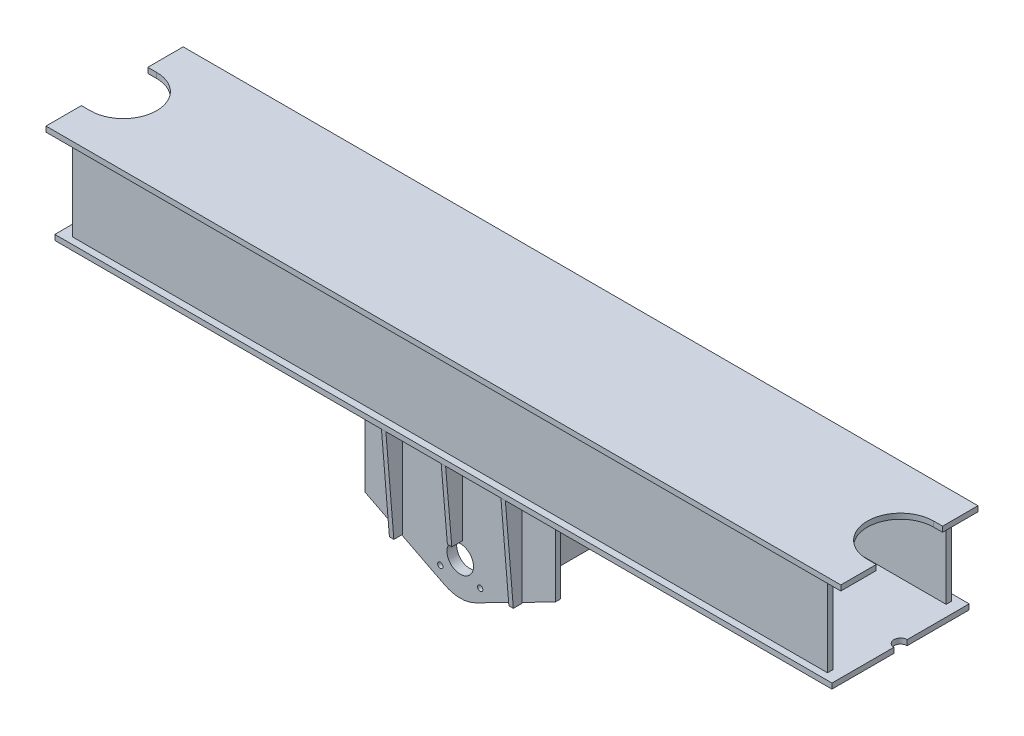
SolidWorks part; units mm, degrees
ref_plane "前视基准面" through (0, 0, 0) normal (0, 0, 1) x (1, 0, 0)
ref_plane "上视基准面" through (0, 0, 0) normal (0, 1, 0) x (1, 0, 0)
ref_plane "右视基准面" through (0, 0, 0) normal (1, 0, 0) x (0, 0, -1)
sketch "草图1" plane through (0, 0, 0) normal (0, 1, 0) x (1, 0, 0)
  line L0 (-1000, 0) -> (49000, 0) construction
  line L1 (0, -1000) -> (0, 49000) construction
  line L2 (-898, 155) -> (898, 155)
  line L3 (-898, -155) -> (898, -155)
  line L4 (898, 155) -> (898, 75)
  line L5 (898, 75) -> (878, 75)
  line L6 (898, -155) -> (898, -75)
  line L7 (878, -75) -> (898, -75)
  line L8 (-898, 155) -> (-898, 75)
  line L9 (-898, 75) -> (-878, 75)
  line L10 (-898, -155) -> (-898, -75)
  line L11 (-898, -75) -> (-878, -75)
  arc A0 (878, 75) -> (878, -75) centre (878, 0) ccw
  arc A1 (-878, 75) -> (-878, -75) centre (-878, 0) cw
  dimension "D3" = 75
  dimension "D5" = 75
  dimension "D1" = 1796
  dimension "D2" = 310
  dimension "D4" = 20
extrude "凸台-拉伸1" add sketch "草图1" along normal blind 12
sketch "草图2" plane through (0, 0, 0) normal (0, -1, 0) x (-1, 0, 0)
  line L0 (0, -1155) -> (0, 48845) construction
  line L1 (898, -155) -> (-898, -155) construction
  line L2 (-1000, 0) -> (49000, 0) construction
  line L3 (-853, 140) -> (853, 140)
  line L4 (853, -140) -> (-853, -140)
  line L5 (853, -140) -> (853, -128)
  line L6 (853, -128) -> (-853, -128)
  line L7 (-853, -140) -> (-853, -128)
  line L8 (-853, 140) -> (-853, 128)
  line L9 (-853, 128) -> (853, 128)
  line L10 (853, 140) -> (853, 128)
  point P5 (0, -155)
  dimension "D1" = 12
  dimension "D2" = 1706
  dimension "D3" = 256
extrude "凸台-拉伸2" add sketch "草图2" along normal blind 190
sketch "草图3" plane through (0, -190, 0) normal (0, -1, 0) x (1, 0, 0)
  line L0 (-898, 155) -> (898, 155) construction
  line L1 (-878, 155) -> (878, 155)
  line L2 (878, 155) -> (878, 15)
  line L3 (-878, -155) -> (878, -155)
  line L4 (878, -155) -> (878, -15)
  line L5 (898, -155) -> (-898, -155) construction
  line L6 (0, -1000) -> (0, 49000) construction
  line L7 (-1000, 0) -> (49000, 0) construction
  line L8 (-878, 155) -> (-878, 15)
  line L9 (-878, -15) -> (-878, -155)
  arc A0 (878, 15) -> (878, -15) centre (878, 0) ccw
  arc A1 (-878, 15) -> (-878, -15) centre (-878, 0) cw
  dimension "D3" = 15
  dimension "D4" = 15
  dimension "D1" = 1756
extrude "凸台-拉伸3" add sketch "草图3" along normal blind 12
sketch "草图4" plane through (0, 0, 0) normal (0, -1, 0) x (-1, 0, 0)
  line L0 (-1000, 0) -> (49000, 0) construction
  line L1 (0, -1000) -> (0, 49000) construction
  line L2 (215, -117) -> (-215, -117)
  line L3 (215, -117) -> (215, -105)
  line L4 (215, -105) -> (-215, -105)
  line L5 (-215, -117) -> (-215, -105)
  line L6 (215, 105) -> (-215, 105)
  line L7 (215, 105) -> (215, 117)
  line L8 (215, 117) -> (-215, 117)
  line L9 (-215, 105) -> (-215, 117)
  dimension "D1" = 12
  dimension "D2" = 12
  dimension "D3" = 430
  dimension "D4" = 210
extrude "凸台-拉伸4" add sketch "草图4" along normal blind 502
sketch "草图5" plane through (0, 0, -117) normal (0, 0, -1) x (-1, 0, 0)
  line L0 (0, -1502) -> (0, 48498) construction
  line L1 (215, -502) -> (-215, -502) construction
  line L2 (215, -202) -> (-215, -202) construction
  line L3 (-215, -382) -> (-215, -502)
  line L4 (-215, -502) -> (-215, -202) construction
  line L5 (-215, -502) -> (215, -502)
  line L6 (215, -502) -> (215, -382)
  line L7 (215, -502) -> (215, -202) construction
  line L8 (215, -382) -> (34.9183, -473.6274)
  line L9 (-215, -382) -> (-34.9183, -473.6274)
  line L10 (878, -202) -> (-878, -202) construction
  line L11 (-959.9136, -482) -> (49040.0864, -482) construction
  line L12 (-899.5404, -440) -> (49100.4596, -440) construction
  circle A0 centre (0, -405) radius 30
  arc A1 (-34.9183, -473.6274) -> (34.9183, -473.6274) centre (0, -405) ccw
  circle A2 centre (-45, -440) radius 6
  circle A3 centre (45, -440) radius 6
  point P5 (0, -502)
  dimension "D1" = 60
  dimension "D8" = 12
  dimension "D2" = 203
  dimension "D3" = 180
  dimension "D4" = 180
  dimension "D5" = 280
  dimension "D6" = 35
  dimension "D7" = 90
extrude "切除-拉伸1" cut sketch "草图5" against normal through all
sketch "草图6" plane through (0, 0, 117) normal (0, 0, 1) x (1, 0, 0)
  line L0 (0, -1405) -> (0, 48595) construction
  line L1 (215, -202) -> (-215, -202) construction
  line L2 (-5, -202) -> (5, -202)
  line L3 (-5, -202) -> (-5, -367)
  line L4 (-5, -367) -> (5, -367)
  line L5 (5, -202) -> (5, -367)
  dimension "D1" = 10
  dimension "D2" = 165
extrude "凸台-拉伸5" add sketch "草图6" along normal blind 38
mirror "镜向1" about plane through (0, 0, 0) normal (0, 0, 1) of "凸台-拉伸5"
sketch "草图7" plane through (-5, 0, 0) normal (-1, 0, 0) x (0, 0, 1)
  line L0 (-155, -202) -> (-155, -367)
  line L1 (-155, -367) -> (-141, -367)
  line L2 (-155, -367) -> (-117, -367) construction
  line L3 (-141, -367) -> (-155, -202)
  line L4 (155, -202) -> (141, -367)
  line L5 (155, -367) -> (117, -367) construction
  line L6 (141, -367) -> (155, -367)
  line L7 (155, -367) -> (155, -202)
  dimension "D1" = 14
  dimension "D2" = 14
extrude "切除-拉伸2" cut sketch "草图7" against normal blind 10
sketch "草图8" plane through (0, -202, 0) normal (0, -1, 0) x (-1, 0, 0)
  line L0 (0, -1000) -> (0, 49000) construction
  line L1 (215, -105) -> (-215, -105) construction
  line L2 (140, -105) -> (130, -105)
  line L3 (140, -105) -> (140, 105)
  line L4 (140, 105) -> (130, 105)
  line L5 (130, -105) -> (130, 105)
  line L6 (-215, 105) -> (215, 105) construction
  line L7 (-215, -105) -> (-34.9183, -105) construction
  line L8 (-130, -105) -> (-140, -105)
  line L9 (-130, -105) -> (-130, 105)
  line L10 (-130, 105) -> (-140, 105)
  line L11 (-140, -105) -> (-140, 105)
  dimension "D1" = 10
  dimension "D2" = 10
  dimension "D3" = 280
extrude "凸台-拉伸6" add sketch "草图8" along normal blind 190
sketch "草图9" plane through (0, -202, 0) normal (0, -1, 0) x (-1, 0, 0)
  line L0 (215, -117) -> (34.9183, -117) construction
  line L1 (140, -155) -> (130, -155)
  line L2 (140, -155) -> (140, -117)
  line L3 (140, -117) -> (130, -117)
  line L4 (130, -155) -> (130, -117)
  line L5 (-34.9183, -117) -> (-215, -117) construction
  line L6 (-130, -155) -> (-140, -155)
  line L7 (-130, -155) -> (-130, -117)
  line L8 (-130, -117) -> (-140, -117)
  line L9 (-140, -155) -> (-140, -117)
  line L10 (215, 117) -> (5, 117) construction
  line L11 (140, 117) -> (130, 117)
  line L12 (140, 117) -> (140, 155)
  line L13 (140, 155) -> (130, 155)
  line L14 (130, 117) -> (130, 155)
  line L16 (-5, 117) -> (-215, 117) construction
  line L17 (-130, 117) -> (-140, 117)
  line L18 (-130, 117) -> (-130, 155)
  line L19 (-130, 155) -> (-140, 155)
  line L20 (-140, 117) -> (-140, 155)
  line L21 (140, -105) -> (140, 105) construction
  line L22 (130, 105) -> (130, -105) construction
  line L23 (5, -155) -> (878, -155) construction
  line L24 (878, 155) -> (5, 155) construction
  line L25 (-5, 155) -> (-878, 155) construction
  line L26 (-130, -105) -> (-130, 105) construction
  line L27 (-140, 105) -> (-140, -105) construction
  line L28 (-878, -155) -> (-5, -155) construction
  line L29 (-140, 105) -> (-140, -105) construction
extrude "凸台-拉伸7" add sketch "草图9" along normal blind 220
sketch "草图10" plane through (140, 0, 0) normal (1, 0, 0) x (0, 0, -1)
  line L0 (-155, -202) -> (-155, -422)
  line L1 (-155, -422) -> (-137, -422)
  line L2 (-117, -422) -> (-155, -422) construction
  line L3 (-137, -422) -> (-155, -202)
  line L4 (155, -202) -> (155, -422)
  line L5 (155, -422) -> (137, -422)
  line L6 (155, -422) -> (117, -422) construction
  line L7 (137, -422) -> (155, -202)
  dimension "D1" = 18
  dimension "D2" = 18
extrude "切除-拉伸3" cut sketch "草图10" against normal blind 18
pattern_linear "阵列(线性)1" count 2 spacing 270 along (-1, 0, 0) of "切除-拉伸3"
sketch "草图11" plane through (0, 0, 0) normal (0, -1, 0) x (-1, 0, 0)
  line L0 (-215, -105) -> (-215, -117) construction
  line L1 (-215, -117) -> (-227, -117)
  line L2 (-215, -117) -> (-215, 117)
  line L3 (-215, 117) -> (-227, 117)
  line L4 (-227, -117) -> (-227, 117)
  line L5 (227, -117) -> (215, -117)
  line L6 (227, -117) -> (227, 117)
  line L7 (227, 117) -> (215, 117)
  line L8 (215, -117) -> (215, 117)
  line L9 (215, -117) -> (215, -105) construction
  line L10 (5, -117) -> (130, -117) construction
  line L11 (136.3852, 117) -> (34.9183, 117) construction
  line L12 (215, -105) -> (140, -105) construction
  line L13 (130, 105) -> (142, 105)
  line L14 (130, 105) -> (130, -105)
  line L15 (130, -105) -> (142, -105)
  line L16 (142, 105) -> (142, -105)
  line L17 (-140, -105) -> (-215, -105) construction
  line L18 (-130, 105) -> (-142, 105)
  line L19 (-130, 105) -> (-130, -105)
  line L20 (-130, -105) -> (-142, -105)
  line L21 (-142, 105) -> (-142, -105)
  dimension "D1" = 12
  dimension "D2" = 12
  dimension "D3" = 12
  dimension "D4" = 12
extrude "凸台-拉伸8" add sketch "草图11" along normal blind 190
sketch "草图12" plane through (0, 0, -105) normal (0, 0, 1) x (1, 0, 0)
  circle A0 centre (0, -405) radius 75
  circle A1 centre (0, -405) radius 30
  circle A2 centre (0, -405) radius 30 construction
  circle A3 centre (-45, -440) radius 6
  circle A4 centre (45, -440) radius 6
  circle A6 centre (-45, -440) radius 6 construction
  circle A7 centre (45, -440) radius 6 construction
  dimension "D1" = 150
extrude "凸台-拉伸9" add sketch "草图12" along normal blind 10
pattern_linear "阵列(线性)2" count 2 spacing 200 along (0, 0, 1) of "凸台-拉伸9"
sketch "草图14" plane through (0, -202, 0) normal (0, -1, 0) x (-1, 0, 0)
  line L0 (34.9183, -105) -> (215, -105) construction
  line L1 (70, -105) -> (60, -105)
  line L2 (70, -105) -> (70, 105)
  line L3 (70, 105) -> (60, 105)
  line L4 (60, -105) -> (60, 105)
  line L5 (215, 105) -> (34.9183, 105) construction
  line L6 (-215, -105) -> (-34.9183, -105) construction
  line L7 (-60, -105) -> (-70, -105)
  line L8 (-60, -105) -> (-60, 105)
  line L9 (-60, 105) -> (-70, 105)
  line L10 (-70, -105) -> (-70, 105)
  line L11 (-130, 105) -> (130, 105) construction
  line L12 (0, -1000) -> (0, 49000) construction
  line L13 (-65, -978.7299) -> (-65, 49021.2701) construction
  line L14 (65, -988.6917) -> (65, 49011.3083) construction
  line L15 (-130, -105) -> (-130, 105) construction
  dimension "D1" = 10
  dimension "D2" = 10
  dimension "D3" = 65
  dimension "D4" = 65
  dimension "D5" = 5
extrude "凸台-拉伸10" add sketch "草图14" along normal blind 100
